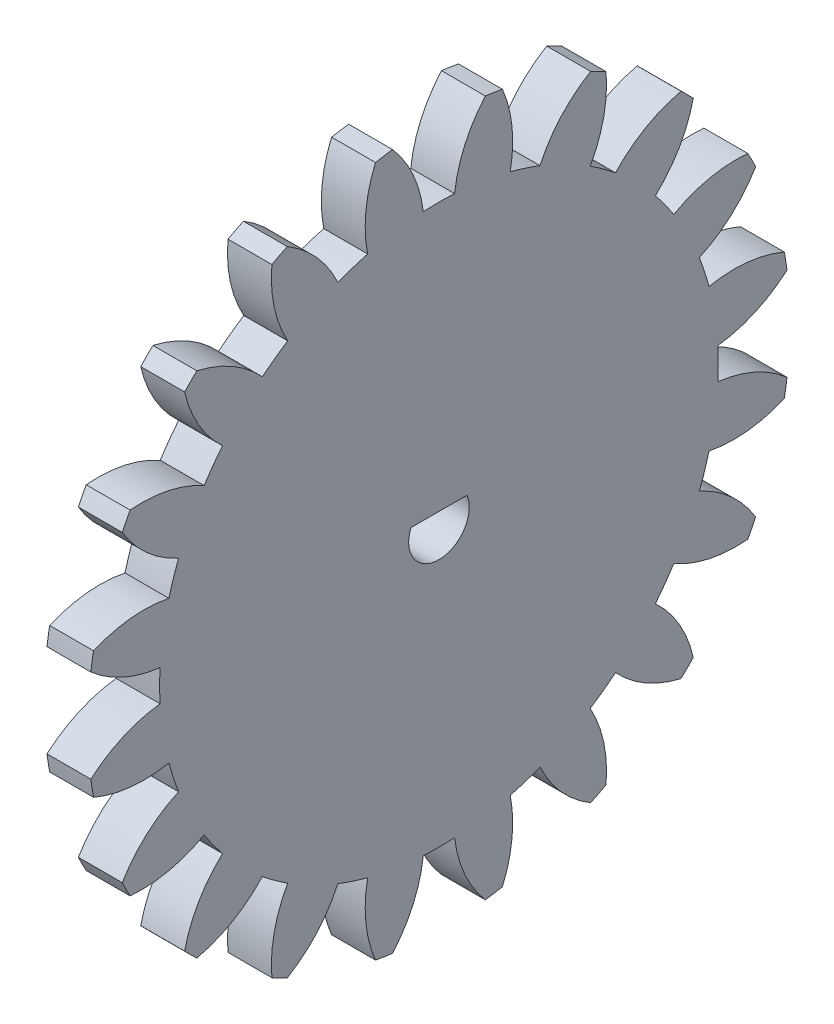
SolidWorks part; units mm, degrees
ref_plane "Plane1" through (0, 0, 0) normal (0, 0, 1) x (1, 0, 0)
ref_plane "Plane2" through (0, 0, 0) normal (0, 1, 0) x (1, 0, 0)
ref_plane "Plane3" through (0, 0, 0) normal (1, 0, 0) x (0, 0, -1)
sketch "HoldingSke" plane through (0, 0, 0) normal (0, 1, 0) x (1, 0, 0)
  line L0 (0, 0) -> (0.2349, -0.0855)
  line L1 (-15, 0) -> (100, 0) construction
  line L2 (0, 0) -> (-2.1039, 2.3779)
  line L3 (0, 0) -> (-11.863, 4.5341)
  line L4 (0, 0) -> (8.1152, 2.9537)
  line L5 (0, 0) -> (-46.8476, -17.4728)
  line L6 (0, 0) -> (-4.5593, -3.0762)
  line L7 (-2.1039, 2.3779) -> (8.6586, 51.2059)
  line L8 (-76.2, 54.61) -> (-76.1, 54.61)
  line L9 (-71.009, 38.7566) -> (-53.1078, 45.2721)
  line L10 (-76.2, 71.12) -> (104.1128, 71.12)
  line L11 (0, 0) -> (-5.5, 0)
  line L12 (-76.2, 101.6) -> (-76.073, 101.6)
  line L13 (24.9733, 27.94) -> (52.9518, 28.4284)
  line L14 (24.9733, 27.94) -> (24.9743, 27.94)
  line L15 (24.9733, 27.94) -> (100.4006, 29.5858)
  line L16 (-63.627, -4) -> (-12.827, -4)
  circle A0 centre (0, 0) radius 0.5
  circle A1 centre (0, 0) radius 34.999
  circle A2 centre (0, 0) radius 37.5
  circle A3 centre (0, 0) radius 0.5
  dimension "MHD" = 69.998
  dimension "Hub_dia" = 75
  dimension "Bore" = 1
  dimension "MBD" = 1
  dimension "Num_teeth" = 20
  dimension "Pitch" = 0.25
  dimension "Overall_len" = 50
  dimension "Show_teeth" = 20
  dimension "Thickness" = 5.5
  dimension "OAL" = 50.0001
  dimension "T_dim" = 0.1
  dimension "Ap" = 20
  dimension "H" = 19.05
  dimension "Pitch_radius" = 180.3128
  dimension "Width" = 5.5
  dimension "Backlash" = 0.127
  dimension "Addendum_fac" = 1
  dimension "Dedendum_fac" = 1.25
  dimension "Clearance_fac" = 0.25
  dimension "Dedendum_add" = 0.001
  dimension "Module" = 4
sketch "BasProSke" plane through (0, 0, 0) normal (0, 1, 0) x (1, 0, 0)
  line L0 (-10, 0) -> (60, 0) construction
  line L1 (0, 0) -> (0, 44)
  line L2 (0, 0) -> (5.5, 0)
  line L3 (5.5, 0) -> (5.5, 44)
  line L4 (5.5, 44) -> (0, 44)
  dimension "Thickness" = 5.5
  dimension "Diameter" = 88
revolve "Base-Revolve" add sketch "BasProSke" angle 360 about L0
sketch "TooCutSke" plane through (0, 0, 0) normal (1, 0, 0) x (0, 0, -1)
  line L1 (0, 0) -> (0, 107) construction
  line L2 (0, 0) -> (-3.3605, 39.8586) construction
  line L3 (0, 0) -> (-12.4815, 78.8048) construction
  line L4 (-3.3605, 39.8586) -> (-6.2407, 39.4024) construction
  arc A0 (1.9617, 34.944) -> (-1.9617, 34.944) centre (0, 0) ccw
  arc A1 (5.8321, 43.6374) -> (-5.8321, 43.6374) centre (0, 0) ccw
  circle A2 centre (0, 0) radius 40 construction
  circle A3 centre (0, 0) radius 37.5877 construction
  arc A4 (-1.9617, 34.944) -> (-5.8321, 43.6374) centre (-17.8525, 33.0775) ccw
  arc A5 (5.8321, 43.6374) -> (1.9617, 34.944) centre (17.8525, 33.0775) ccw
  dimension "Root_dia" = 69.998
  dimension "Overcut_dia" = 88.0508
  dimension "Pitch_dia" = 80
  dimension "Base_dia" = 75.1754
  dimension "Flank_rad" = 16
  dimension "Half_ang" = 9
  dimension "Half_CT" = 2.9161
extrude "ToothCut" cut sketch "TooCutSke" along normal through all
fillet "Breaks" [suppressed] radius 0.08
fillet "RootFillets" [suppressed] radius 1.001
pattern_circular "TeethCuts" count 20 every 18 about axis through (-10, 0, 0) along (1, 0, 0) of "ToothCut", "RootFillets", "Breaks"
sketch "HubNeaOneSke" plane through (0, 0, 0) normal (-1, 0, 0) x (0, 0, 1)
  circle A0 centre (0, 0) radius 34.999
  dimension "Diameter" = 69.998
extrude "HubNearOne" [suppressed] add sketch "HubNeaOneSke" along normal blind 44.5001
sketch "HubNeaBotSke" plane through (0, 0, 0) normal (-1, 0, 0) x (0, 0, 1)
  circle A0 centre (0, 0) radius 34.999
  dimension "Diameter" = 69.998
extrude "HubNearBoth" [suppressed] add sketch "HubNeaBotSke" along normal blind 22.25
ref_plane "FarPln" through (5.5, 0, 0) normal (1, 0, 0) x (0, 0, -1)
sketch "HubFarSke" plane through (5.5, 0, 0) normal (1, 0, 0) x (0, 0, -1)
  circle A0 centre (0, 0) radius 34.999
  dimension "Diameter" = 69.998
extrude "HubFar" [suppressed] add sketch "HubFarSke" along normal blind 22.25
sketch "BorSke" plane through (0, 0, 0) normal (1, 0, 0) x (0, 0, -1)
  circle A0 centre (0, 0) radius 0.5
  dimension "Diameter" = 1
extrude "Bore" cut sketch "BorSke" along normal mid plane 100.0001
sketch "KeySke" plane through (0, 0, 0) normal (1, 0, 0) x (0, 0, -1)
  line L0 (-0.05, 0) -> (-0.05, 0.6)
  line L1 (-0.05, 0.6) -> (0.05, 0.6)
  line L2 (0.05, 0.6) -> (0.05, 0)
  line L3 (0, 0) -> (0, 34) construction
  line L4 (-0.05, 0) -> (0.05, 0)
  dimension "Offset" = 0.6
  dimension "Width" = 0.1
extrude "Keyway" [suppressed] cut sketch "KeySke" along normal mid plane 100.0001
pattern_circular "Keyway2" [suppressed] count 2 every 90 about axis through (-10, 0, 0) along (1, 0, 0)
sketch "Croquis1" plane through (5.5, 0, 0) normal (1, 0, 0) x (0, 0, -1)
  line L0 (0, -3.795) -> (0, 1.435) construction
  line L1 (-3.5132, 1.435) -> (3.5132, 1.435)
  arc A0 (-3.5132, 1.435) -> (3.5132, 1.435) centre (0, 0) ccw
  dimension "D1" = 7.59
  dimension "D2" = 5.23
extrude "Cortar-Extruir1" cut sketch "Croquis1" against normal blind 5.5
sketch "Croquis2" plane through (5.5, 0, 0) normal (1, 0, 0) x (0, 0, -1)
  line L0 (-0.5, 0) -> (0.5, 0)
  arc A0 (0.5, 0) -> (-0.5, 0) centre (0, 0) ccw
extrude "Saliente-Extruir1" [suppressed] add sketch "Croquis2" against normal blind 5.5
equation "' \"Module@HoldingSke\" = 6.35"
equation "' \"Num_teeth@HoldingSke\" = 12"
equation "' \"Ap@HoldingSke\" =  20"
equation "' \"Ap@HoldingSke\" = 20"
equation "' \"Width@HoldingSke\" = 0.5 * 25.4"
equation "' \"Hub_dia@HoldingSke\"= 1 * 25.4"
equation "' \"Hub_dia@HoldingSke\" = 1 * 25.4"
equation "' \"Overall_len@HoldingSke\" = 1.0 * 25.4"
equation "' \"Bore@HoldingSke\" = 0.75 * 25.4"
equation "' \"T_dim@HoldingSke\" = 0.1 * 25.4"
equation "' \"Width@KeySke\" = 0.25 * 25.4"
equation "' \"Show_teeth@HoldingSke\" = 13"
equation "' \"Backlash@HoldingSke\" = 0.009 * 25.4"
equation "' \"Addendum_fac@HoldingSke\" = 1.0"
equation "' \"Dedendum_fac@HoldingSke\" = 1.25"
equation "' \"Dedendum_add@HoldingSke\" = 0.00005 * 25.4"
equation "' \"Clearance_fac@HoldingSke\" = 0.25"
equation "\"Pitch@HoldingSke\" = 1 / \"Module@HoldingSke\""
equation "\"Overcut_dia@TooCutSke\" = (\"Num_teeth@HoldingSke\" + 2 * \"Addendum_fac@HoldingSke\") / \"Pitch@HoldingSke\" + 0.002 * 25.4"
equation "\"Pitch_dia@TooCutSke\" = \"Num_teeth@HoldingSke\" / \"Pitch@HoldingSke\""
equation "\"Base_dia@TooCutSke\" = \"Num_teeth@HoldingSke\" / \"Pitch@HoldingSke\" * cos((\"Ap@HoldingSke\"  * 3.14159265 / 180))"
equation "\"Root_dia@TooCutSke\" = (\"Num_teeth@HoldingSke\" + 2) / \"Pitch@HoldingSke\" - 2 * (\"Addendum_fac@HoldingSke\" + \"Dedendum_fac@HoldingSke\") / \"Pitch@HoldingSke\" - \"Dedendum_add@HoldingSke\" * 2"
equation "\"Half_ang@TooCutSke\" = 180 / \"Num_teeth@HoldingSke\""
equation "\"Half_CT@TooCutSke\" = \"Num_teeth@HoldingSke\" / \"Pitch@HoldingSke\" * sin((3.14159265 / 2 / \"Num_teeth@HoldingSke\")) / 2 - 7 * \"Backlash@HoldingSke\" / 4"
equation "\"Flank_rad@TooCutSke\" = \"Num_teeth@HoldingSke\" / \"Pitch@HoldingSke\" / 5"
equation "\"Radius@RootFillets\" = \"Clearance_fac@HoldingSke\" / \"Pitch@HoldingSke\" + \"Dedendum_add@HoldingSke\""
equation "\"Break_rad@Breaks\" = 0.02 / \"Pitch@HoldingSke\""
equation "\"Thickness@HoldingSke\" = \"Width@HoldingSke\""
equation "\"OAL@HoldingSke\" = \"Thickness@HoldingSke\""
equation "\"MHD@HoldingSke\" = (\"Num_teeth@HoldingSke\" + 2) / \"Pitch@HoldingSke\" - 2 * (\"Addendum_fac@HoldingSke\" + \"Dedendum_fac@HoldingSke\")  / \"Pitch@HoldingSke\" - \"Dedendum_add@HoldingSke\" * 2"
equation "\"MBD@HoldingSke\" = (\"Num_teeth@HoldingSke\" + 2) / \"Pitch@HoldingSke\" - 2 * (\"Addendum_fac@HoldingSke\" + \"Dedendum_fac@HoldingSke\")  / \"Pitch@HoldingSke\" - \"Dedendum_add@HoldingSke\" * 2 - 0.002 * 25.4"
equation "\"MHD@HoldingSke\" = ((sgn( \"MHD@HoldingSke\" - \"Hub_dia@HoldingSke\" )-1)*( \"MHD@HoldingSke\" - \"Hub_dia@HoldingSke\" ))/-2+ \"Hub_dia@HoldingSke\""
equation "\"MBD@HoldingSke\" = ((sgn( \"MBD@HoldingSke\" - \"Bore@HoldingSke\" )-1)*( \"MBD@HoldingSke\" - \"Bore@HoldingSke\" ))/-2+ \"Bore@HoldingSke\""
equation "\"OAL@HoldingSke\" = ((sgn( \"OAL@HoldingSke\" - \"Overall_len@HoldingSke\" )+1)*( \"OAL@HoldingSke\" - \"Overall_len@HoldingSke\" ))/2 + \"Overall_len@HoldingSke\" + 0.000002 * 25.4"
equation "\"Num_teeth@TeethCuts\" = int( \"Show_teeth@HoldingSke\" ) + 1"
equation "\"Num_teeth@TeethCuts\" = ((sgn( \"Num_teeth@TeethCuts\" - \"Num_teeth@HoldingSke\" )-1)*( \"Num_teeth@TeethCuts\" - \"Num_teeth@HoldingSke\" ))/-2+ \"Num_teeth@HoldingSke\""
equation "\"Num_teeth@TeethCuts\" = ((sgn( \"Num_teeth@TeethCuts\" - 2.0)+1)*( \"Num_teeth@TeethCuts\" - 2.0))/2 +2.0"
equation "\"Angle@TeethCuts\" = 360.0 / \"Num_teeth@HoldingSke\""
equation "\"Diameter@BasProSke\" = (\"Num_teeth@HoldingSke\" + 2 * \"Addendum_fac@HoldingSke\") / \"Pitch@HoldingSke\""
equation "\"Thickness@BasProSke\"  = \"Thickness@HoldingSke\""
equation "' \"Fillet_rad@BasProSke\" =  \"Thickness@HoldingSke\" * 0.05"
equation "' \"Fillet_rad@BasProSke\" = \"Thickness@HoldingSke\" * 0.05"
equation "\"MHD@HoldingSke\" = ((sgn( \"MHD@HoldingSke\" - \"Root_dia@TooCutSke\" )-1)*( \"MHD@HoldingSke\" - \"Root_dia@TooCutSke\" ))/-2+ \"Root_dia@TooCutSke\""
equation "\"Diameter@HubNeaOneSke\" = \"MHD@HoldingSke\""
equation "\"Length@HubNearOne\" = \"OAL@HoldingSke\" - \"Thickness@BasProSke\""
equation "\"Diameter@HubNeaBotSke\" = \"MHD@HoldingSke\""
equation "\"Length@HubNearBoth\" = ( \"OAL@HoldingSke\" - \"Thickness@BasProSke\" ) / 2.0"
equation "\"Thickness@FarPln\" = \"Thickness@BasProSke\""
equation "\"Diameter@HubFarSke\" = \"MHD@HoldingSke\""
equation "\"Length@HubFar\" = ( \"OAL@HoldingSke\" - \"Thickness@BasProSke\" ) / 2.0"
equation "\"Diameter@BorSke\" = \"MBD@HoldingSke\""
equation "\"D1@Bore\" = \"OAL@HoldingSke\" * 2.0"
equation "\"D1@Keyway\" = \"OAL@HoldingSke\" * 2.0"
equation "\"Offset@KeySke\" = \"T_dim@HoldingSke\" + \"MBD@HoldingSke\" / 2.0"
